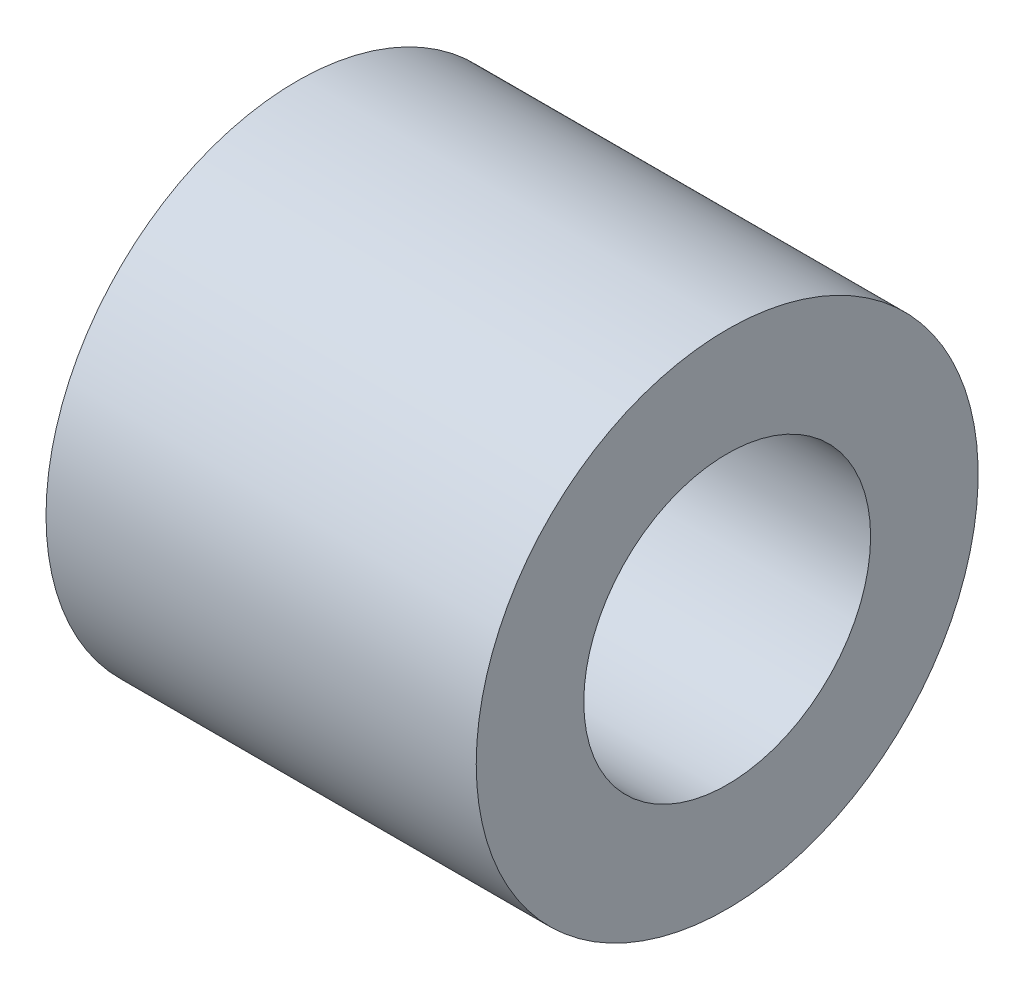
SolidWorks part; units mm, degrees
ref_plane "Front" through (0, 0, 0) normal (0, 0, 1) x (1, 0, 0)
ref_plane "Top" through (0, 0, 0) normal (0, 1, 0) x (1, 0, 0)
ref_plane "Right" through (0, 0, 0) normal (1, 0, 0) x (0, 0, -1)
sketch "Sketch2" plane through (0, 0, 0) normal (0, 0, 1) x (1, 0, 0)
  line L0 (0, 0) -> (27.8004, 0) construction
  line L2 (0, 0) -> (12, 0)
  line L4 (0, 4) -> (12, 4)
  line L6 (0, 4) -> (12, 4)
  line L7 (0, 4) -> (0, 7)
  line L8 (0, 7) -> (12, 7)
  line L9 (12, 4) -> (12, 7)
  dimension "D2" = 8
  dimension "D3" = 14
revolve "Revolve2" add sketch "Sketch2" angle 360 about L0
